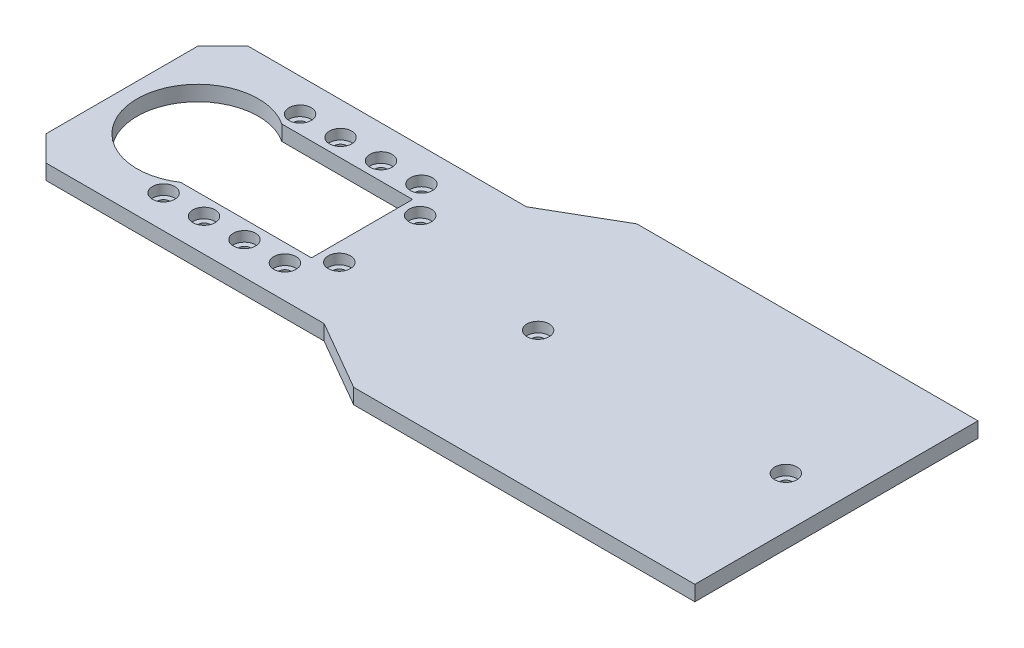
SolidWorks part; units mm, degrees
ref_plane "Front" through (0, 0, 0) normal (0, 0, 1) x (1, 0, 0)
ref_plane "Top" through (0, 0, 0) normal (0, 1, 0) x (1, 0, 0)
ref_plane "Right" through (0, 0, 0) normal (1, 0, 0) x (0, 0, -1)
sketch "草图1" plane through (0, 0, 0) normal (0, 1, 0) x (1, 0, 0)
  line L0 (-45.7157, 114) -> (45.7157, 114)
  line L1 (-74, 0) -> (74, 0) construction
  line L2 (74, -30) -> (91.3205, -20)
  line L3 (91.3205, -20) -> (146.3205, -20)
  line L4 (151.3205, -15) -> (151.3205, 15)
  line L5 (-60, 100) -> (60, -100) construction
  line L6 (-60, -100) -> (60, 100) construction
  line L7 (74, -30) -> (74, -85.7157)
  line L8 (-45.7157, -114) -> (45.7157, -114)
  line L9 (-74, 85.7157) -> (-74, 30)
  line L10 (146.3205, 20) -> (91.3205, 20)
  line L11 (74, 30) -> (91.3205, 20)
  line L12 (0, 100) -> (0, -100) construction
  line L13 (-74, 30) -> (-91.3205, 20)
  line L14 (-146.3205, 20) -> (-91.3205, 20)
  line L15 (-151.3205, -15) -> (-151.3205, 15)
  line L16 (-91.3205, -20) -> (-146.3205, -20)
  line L17 (-74, -30) -> (-91.3205, -20)
  line L18 (-74, -30) -> (-74, -85.7157)
  line L19 (74, 85.7157) -> (74, 30)
  line L20 (91.6777, 152.8909) -> (112.8909, 131.6777)
  line L21 (74, 85.7157) -> (112.8909, 124.6066)
  line L22 (45.7157, 114) -> (84.6066, 152.8909)
  line L23 (-74, 85.7157) -> (-112.8909, 124.6066)
  line L24 (-91.6777, 152.8909) -> (-112.8909, 131.6777)
  line L25 (-45.7157, 114) -> (-84.6066, 152.8909)
  line L26 (74, -85.7157) -> (112.8909, -124.6066)
  line L27 (91.6777, -152.8909) -> (112.8909, -131.6777)
  line L28 (45.7157, -114) -> (84.6066, -152.8909)
  line L29 (-74, -85.7157) -> (-112.8909, -124.6066)
  line L30 (-91.6777, -152.8909) -> (-112.8909, -131.6777)
  line L31 (-45.7157, -114) -> (-84.6066, -152.8909)
  line L32 (-84.6066, 152.8909) -> (-91.6777, 152.8909)
  line L33 (-112.8909, 131.6777) -> (-112.8909, 124.6066)
  line L34 (-151.3205, 15) -> (-146.3205, 20)
  line L35 (-146.3205, -20) -> (-151.3205, -15)
  line L36 (-112.8909, -124.6066) -> (-112.8909, -131.6777)
  line L37 (-84.6066, -152.8909) -> (-91.6777, -152.8909)
  line L38 (84.6066, -152.8909) -> (91.6777, -152.8909)
  line L39 (112.8909, -131.6777) -> (112.8909, -124.6066)
  line L40 (146.3205, -20) -> (151.3205, -15)
  line L41 (151.3205, 15) -> (146.3205, 20)
  line L42 (112.8909, 124.6066) -> (112.8909, 131.6777)
  line L43 (84.6066, 152.8909) -> (91.6777, 152.8909)
  point P0 (0, 0)
  point P12 (74, 30)
  point P16 (74, -30)
extrude "凸台-拉伸1" add sketch "草图1" along normal blind 3
sketch "草图2" plane through (0, 3, 0) normal (0, 1, 0) x (1, 0, 0)
  line L0 (151.3205, 0) -> (87.3942, 0) construction
  line L1 (151.3205, -15) -> (151.3205, 15) construction
  line L2 (103.8205, -10) -> (103.8205, 10)
  line L3 (103.8205, 10) -> (129.6873, 10)
  line L4 (103.8205, -10) -> (129.6873, -10)
  arc A0 (129.6873, -10) -> (129.6873, 10) centre (136.3205, 0) ccw
  point P11 (103.8205, 0)
  dimension "D2" = 24
  dimension "D1" = 15
  dimension "D3" = 20
  dimension "D4" = 32.5
extrude "切除-拉伸1" cut sketch "草图2" against normal up to next
sketch "草图3" plane through (0, 3, 0) normal (0, 1, 0) x (1, 0, 0)
  line L0 (129.6873, 10) -> (103.8205, 10) construction
  line L1 (103.8205, 10) -> (103.8205, -10) construction
  line L2 (151.3205, 0) -> (86.0016, 0) construction
  line L3 (151.3205, -15) -> (151.3205, 15) construction
  point P0 (105.5705, 13.5)
  point P10 (100.3205, 8)
  point P12 (113.5705, 13.5)
  point P13 (121.5705, 13.5)
  point P14 (129.5705, 13.5)
  point P15 (129.5705, -13.5)
  point P16 (121.5705, -13.5)
  point P17 (113.5705, -13.5)
  point P18 (105.5705, -13.5)
  point P19 (100.3205, -8)
  dimension "D1" = 3.5
  dimension "D2" = 1.75
  dimension "D4" = 3.5
  dimension "D5" = 2
  dimension "D3" = 4
hole_wizard "M2 凹头盖螺钉的柱形沉头孔2" positions "3D草图1" profile "草图9" counterbore size "M2" standard "ANSI Metric" end condition through all
sketch3d "3D草图1"
  point P0 (100.3205, 3, -8)
  point P3 (105.5705, 3, -13.5)
  point P6 (113.5705, 3, -13.5)
  point P9 (121.5705, 3, -13.5)
  point P12 (129.5705, 3, -13.5)
  point P15 (100.3205, 3, 8)
  point P18 (105.5705, 3, 13.5)
  point P21 (113.5705, 3, 13.5)
  point P24 (121.5705, 3, 13.5)
  point P27 (129.5705, 3, 13.5)
sketch "草图9" plane through (100.3205, 3, -8) normal (1, 0, 0) x (0, 0, 1)
  line L0 (0, 0) -> (0, 3)
  line L1 (0, 3) -> (1.2, 3)
  line L3 (1.2, 3) -> (1.2, 2)
  line L4 (1.2, 2) -> (2.2, 2)
  line L5 (2.2, 2) -> (2.2, 0)
  line L7 (2.2, 0) -> (0, 0)
  line L11 (0, -6.35) -> (0, 107.95) construction
  dimension "通孔孔直径" = 2.4
  dimension "通孔孔深度" = 3
  dimension "柱形沉头孔直径" = 4.4
  dimension "柱形沉头孔深度" = 2
sketch "草图10" plane through (0, 3, 0) normal (0, 1, 0) x (1, 0, 0)
  line L0 (102.2843, 142.2843) -> (57.3662, 97.3662) construction
  line L1 (112.8909, 131.6777) -> (91.6777, 152.8909) construction
  line L2 (75.7678, 101.6256) -> (61.6256, 115.7678)
  line L3 (61.6256, 115.7678) -> (79.9162, 134.0583)
  line L4 (75.7678, 101.6256) -> (94.0583, 119.9162)
  arc A0 (94.0583, 119.9162) -> (79.9162, 134.0583) centre (91.6777, 131.6777) ccw
  point P9 (68.6967, 108.6967)
  dimension "D1" = 15
  dimension "D2" = 32.5
extrude "切除-拉伸2" cut sketch "草图10" against normal up to next
sketch "草图16" plane through (0, 3, 0) normal (0, 1, 0) x (1, 0, 0)
  line L0 (102.2843, 142.2843) -> (58.019, 98.019) construction
  line L1 (112.8909, 131.6777) -> (91.6777, 152.8909) construction
  line L2 (61.6256, 115.7678) -> (75.7678, 101.6256) construction
  line L3 (79.9162, 134.0583) -> (61.6256, 115.7678) construction
  line L4 (60.3882, 119.4801) -> (80.2149, 139.3067) construction
  point P0 (60.3882, 119.4801)
  point P1 (60.565, 111.8787)
  point P12 (66.045, 125.1369)
  point P13 (71.7019, 130.7938)
  point P14 (77.3588, 136.4506)
  point P15 (96.4506, 117.3588)
  point P16 (90.7938, 111.7019)
  point P17 (85.1369, 106.045)
  point P18 (79.4801, 100.3882)
  point P19 (71.8787, 100.565)
  dimension "D1" = 3.5
  dimension "D2" = 2
  dimension "D3" = 1.75
  dimension "D4" = 3.5
  dimension "D5" = 8
  dimension "D6" = 8
  dimension "D7" = 8
hole_wizard "M2 凹头盖螺钉的柱形沉头孔3" positions "3D草图3" profile "草图17" counterbore size "M2" standard "ANSI Metric" end condition through all
sketch3d "3D草图3"
  point P0 (60.3882, 3, -119.4801)
  point P3 (66.045, 3, -125.1369)
  point P6 (71.7019, 3, -130.7938)
  point P9 (77.3588, 3, -136.4506)
  point P12 (60.565, 3, -111.8787)
  point P15 (71.8787, 3, -100.565)
  point P18 (79.4801, 3, -100.3882)
  point P21 (85.1369, 3, -106.045)
  point P24 (90.7938, 3, -111.7019)
  point P27 (96.4506, 3, -117.3588)
sketch "草图17" plane through (60.3882, 3, -119.4801) normal (1, 0, 0) x (0, 0, 1)
  line L0 (0, 0) -> (0, 3)
  line L1 (0, 3) -> (1.2, 3)
  line L3 (1.2, 3) -> (1.2, 2)
  line L4 (1.2, 2) -> (2.2, 2)
  line L5 (2.2, 2) -> (2.2, 0)
  line L7 (2.2, 0) -> (0, 0)
  line L11 (0, -6.35) -> (0, 107.95) construction
  dimension "通孔孔直径" = 2.4
  dimension "通孔孔深度" = 3
  dimension "柱形沉头孔直径" = 4.4
  dimension "柱形沉头孔深度" = 2
mirror "镜向5" about plane through (0, 0, 0) normal (1, 0, 0) of "切除-拉伸1", "M2 凹头盖螺钉的柱形沉头孔2"
mirror "镜向6" about plane through (0, 0, 0) normal (1, 0, 0) of "切除-拉伸2", "M2 凹头盖螺钉的柱形沉头孔3"
mirror "镜向7" about plane through (0, 0, 0) normal (0, 0, 1) of "切除-拉伸2", "M2 凹头盖螺钉的柱形沉头孔3", "镜向6"
sketch "草图18" plane through (0, 3, 0) normal (0, 1, 0) x (1, 0, 0)
  line L0 (0, 114) -> (0, -114) construction
  line L1 (45.7157, 114) -> (-45.7157, 114) construction
  line L2 (-45.7157, -114) -> (45.7157, -114) construction
  line L3 (-151.3205, 0) -> (151.3205, 0) construction
  line L4 (-151.3205, 15) -> (-151.3205, -15) construction
  line L5 (-60, -28) -> (-15, -28)
  line L6 (-15, -28) -> (-15, -63)
  line L7 (-15, -63) -> (-60, -83)
  line L8 (-60, -83) -> (-60, -28)
  line L12 (10, -94) -> (30, -94)
  line L13 (-10, -94) -> (-30, -94)
  line L14 (-10, -94) -> (-10, -104)
  line L15 (-10, -104) -> (-30, -104)
  line L16 (-30, -94) -> (-30, -104)
  line L17 (-10, -94) -> (-30, -104) construction
  line L18 (-10, -104) -> (-30, -94) construction
  line L19 (10, -104) -> (30, -104)
  line L20 (10, -94) -> (10, -104)
  line L21 (30, -94) -> (30, -104)
  line L22 (15, -63) -> (60, -83)
  line L23 (60, -83) -> (60, -28)
  line L25 (15, -28) -> (15, -63)
  line L26 (60, -28) -> (15, -28)
  line L27 (-10, 104) -> (-30, 104)
  line L28 (-30, 94) -> (-30, 104)
  line L29 (-10, 94) -> (-30, 94)
  line L30 (-10, 94) -> (-10, 104)
  line L31 (30, 94) -> (30, 104)
  line L32 (10, 104) -> (30, 104)
  line L33 (10, 94) -> (10, 104)
  line L34 (10, 94) -> (30, 94)
  line L35 (15, 63) -> (60, 83)
  line L36 (60, 83) -> (60, 28)
  line L37 (60, 28) -> (15, 28)
  line L38 (15, 28) -> (15, 63)
  line L39 (-15, 28) -> (-15, 63)
  line L40 (-60, 28) -> (-15, 28)
  line L41 (-60, 83) -> (-60, 28)
  line L42 (-15, 63) -> (-60, 83)
  point P17 (-20, -99)
  point P32 (0, -20)
  point P33 (0, -10)
  dimension "D5" = 60
  dimension "D6" = 45
  dimension "D7" = 55
  dimension "D8" = 35
  dimension "D9" = 20
  dimension "D10" = 10
  dimension "D11" = 10
  dimension "D12" = 10
extrude "切除-拉伸3" cut sketch "草图18" against normal up to next
sketch "草图19" plane through (0, 3, 0) normal (0, 1, 0) x (1, 0, 0)
  line L0 (0, 114) -> (0, -114) construction
  line L1 (45.7157, 114) -> (-45.7157, 114) construction
  line L2 (-45.7157, -114) -> (45.7157, -114) construction
  line L3 (-151.3205, 0) -> (151.3205, 0) construction
  line L4 (-151.3205, 15) -> (-151.3205, -15) construction
  line L5 (-10, 94) -> (-10, 104) construction
  point P0 (-20, 109)
  point P14 (20, 109)
  point P15 (20, -109)
  point P16 (-20, -109)
  point P17 (-20, 0)
  point P18 (20, 0)
  dimension "D1" = 5
  dimension "D2" = 10
hole_wizard "M2 凹头盖螺钉的柱形沉头孔4" positions "3D草图4" profile "草图20" counterbore size "M2" standard "ANSI Metric" end condition through all
sketch3d "3D草图4"
  point P0 (-20, 3, 109)
  point P3 (20, 3, 109)
  point P6 (-20, 3, -109)
  point P9 (20, 3, -109)
sketch "草图20" plane through (-20, 3, 109) normal (1, 0, 0) x (0, 0, 1)
  line L0 (0, 0) -> (0, 3)
  line L1 (0, 3) -> (1.2, 3)
  line L3 (1.2, 3) -> (1.2, 2)
  line L4 (1.2, 2) -> (2.2, 2)
  line L5 (2.2, 2) -> (2.2, 0)
  line L7 (2.2, 0) -> (0, 0)
  line L11 (0, -6.35) -> (0, 107.95) construction
  dimension "通孔孔直径" = 2.4
  dimension "通孔孔深度" = 3
  dimension "柱形沉头孔直径" = 4.4
  dimension "柱形沉头孔深度" = 2
sketch "草图21" plane through (0, 3, 0) normal (0, 1, 0) x (1, 0, 0)
  line L0 (-74, 85.7157) -> (-74, 30) construction
  line L1 (74, 30) -> (74, 85.7157) construction
  line L2 (-60, 28) -> (-15, 28) construction
  line L3 (15, 28) -> (60, 28) construction
  point P0 (-69, 40)
  point P1 (69, 40)
  point P6 (-69, 0)
  point P11 (69, 0)
  dimension "D1" = 5
  dimension "D2" = 5
  dimension "D3" = 12
  dimension "D4" = 12
  dimension "D5" = 40
hole_wizard "M2 凹头盖螺钉的柱形沉头孔5" positions "3D草图5" profile "草图22" counterbore size "M2" standard "ANSI Metric" end condition through all
sketch3d "3D草图5"
  point P0 (-69, 3, -40)
  point P3 (69, 3, -40)
sketch "草图22" plane through (-69, 3, -40) normal (1, 0, 0) x (0, 0, 1)
  line L0 (0, 0) -> (0, 3)
  line L1 (0, 3) -> (1.2, 3)
  line L3 (1.2, 3) -> (1.2, 2)
  line L4 (1.2, 2) -> (2.2, 2)
  line L5 (2.2, 2) -> (2.2, 0)
  line L7 (2.2, 0) -> (0, 0)
  line L11 (0, -6.35) -> (0, 107.95) construction
  dimension "通孔孔直径" = 2.4
  dimension "通孔孔深度" = 3
  dimension "柱形沉头孔直径" = 4.4
  dimension "柱形沉头孔深度" = 2
mirror "镜向8" about plane through (0, 0, 0) normal (0, 0, 1) of "M2 凹头盖螺钉的柱形沉头孔5"
hole_wizard "M2 凹头盖螺钉的柱形沉头孔6" positions "3D草图6" profile "草图23" counterbore size "M2" standard "ANSI Metric" end condition through all
sketch3d "3D草图6"
  point P0 (-69, 3, 0)
  point P3 (69, 3, 0)
sketch "草图23" plane through (-69, 3, 0) normal (1, 0, 0) x (0, 0, 1)
  line L0 (0, 0) -> (0, 3)
  line L1 (0, 3) -> (1.2, 3)
  line L3 (1.2, 3) -> (1.2, 2)
  line L4 (1.2, 2) -> (2.2, 2)
  line L5 (2.2, 2) -> (2.2, 0)
  line L7 (2.2, 0) -> (0, 0)
  line L11 (0, -6.35) -> (0, 107.95) construction
  dimension "通孔孔直径" = 2.4
  dimension "通孔孔深度" = 3
  dimension "柱形沉头孔直径" = 4.4
  dimension "柱形沉头孔深度" = 2
sketch "草图24" plane through (0, 3, 0) normal (0, 1, 0) x (1, 0, 0)
  line L3 (-10, 28) -> (10, 28)
  line L4 (-10, 28) -> (-10, -28)
  line L5 (-10, -28) -> (10, -28)
  line L6 (10, 28) -> (10, -28)
  line L7 (-10, 28) -> (10, -28) construction
  line L8 (-10, -28) -> (10, 28) construction
  point P0 (0, 0)
  dimension "D1" = 20
  dimension "D2" = 56
extrude "切除-拉伸4" cut sketch "草图24" against normal blind 10
hole_wizard "M2 凹头盖螺钉的柱形沉头孔7" positions "3D草图7" profile "草图25" counterbore size "M2" standard "ANSI Metric" end condition through all
sketch3d "3D草图7"
  point P0 (-20, 3, 0)
  point P3 (20, 3, 0)
sketch "草图25" plane through (-20, 3, 0) normal (1, 0, 0) x (0, 0, 1)
  line L0 (0, 0) -> (0, 3)
  line L1 (0, 3) -> (1.2, 3)
  line L3 (1.2, 3) -> (1.2, 2)
  line L4 (1.2, 2) -> (2.2, 2)
  line L5 (2.2, 2) -> (2.2, 0)
  line L7 (2.2, 0) -> (0, 0)
  line L11 (0, -6.35) -> (0, 107.95) construction
  dimension "通孔孔直径" = 2.4
  dimension "通孔孔深度" = 3
  dimension "柱形沉头孔直径" = 4.4
  dimension "柱形沉头孔深度" = 2
sketch "草图26" plane through (0, 3, 0) normal (0, 1, 0) x (1, 0, 0)
  line L0 (-10, -28) -> (10, -28) construction
  line L1 (-151.3205, 28) -> (0, 28)
  line L2 (-151.3205, 28) -> (-151.3205, -28)
  line L3 (-151.3205, -28) -> (0, -28)
  line L4 (0, 28) -> (0, -28)
extrude "切除-拉伸6" cut sketch "草图26" against normal blind 10 flip side to cut
